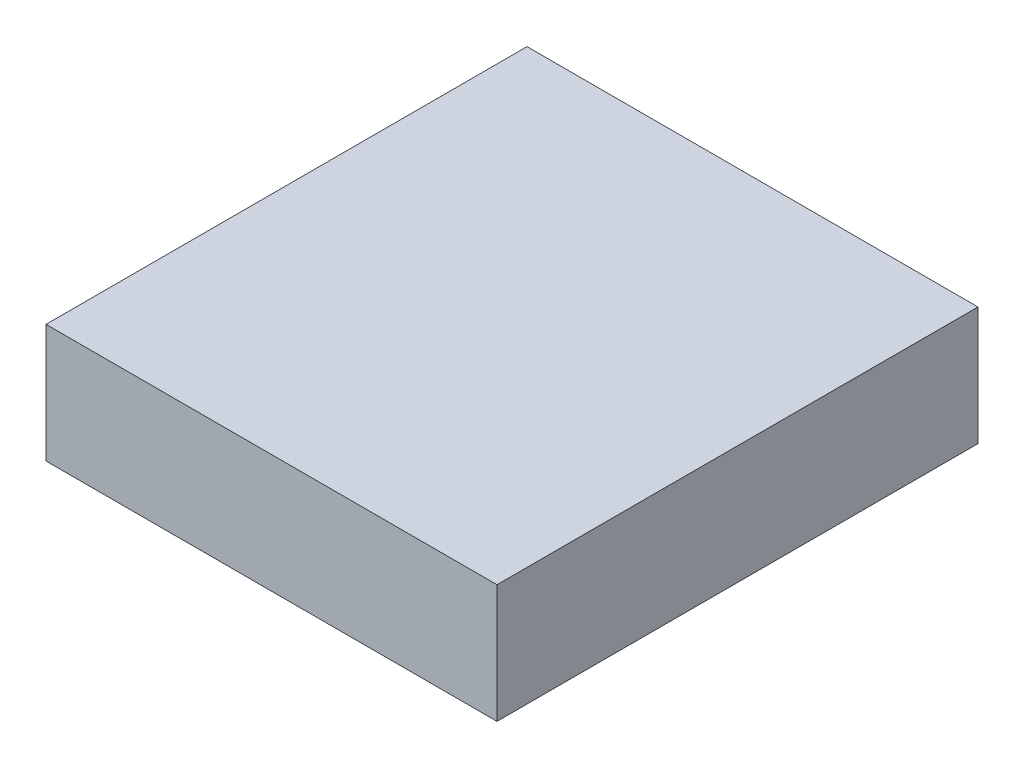
SolidWorks part; units mm, degrees
ref_plane "Front Plane" through (0, 0, 0) normal (0, 0, 1) x (1, 0, 0)
ref_plane "Top Plane" through (0, 0, 0) normal (0, 1, 0) x (1, 0, 0)
ref_plane "Right Plane" through (0, 0, 0) normal (1, 0, 0) x (0, 0, -1)
sketch "Sketch1" plane through (0, 0, 0) normal (0, 1, 0) x (1, 0, 0)
  line L1 (-47.625, 50.8) -> (47.625, 50.8)
  line L2 (-47.625, 50.8) -> (-47.625, -50.8)
  line L3 (-47.625, -50.8) -> (47.625, -50.8)
  line L4 (47.625, 50.8) -> (47.625, -50.8)
  line L5 (-47.625, 50.8) -> (47.625, -50.8) construction
  line L6 (-47.625, -50.8) -> (47.625, 50.8) construction
  point P0 (0, 0)
  dimension "D1" = 95.25
  dimension "D2" = 101.6
extrude "Boss-Extrude1" add sketch "Sketch1" along normal blind 25
